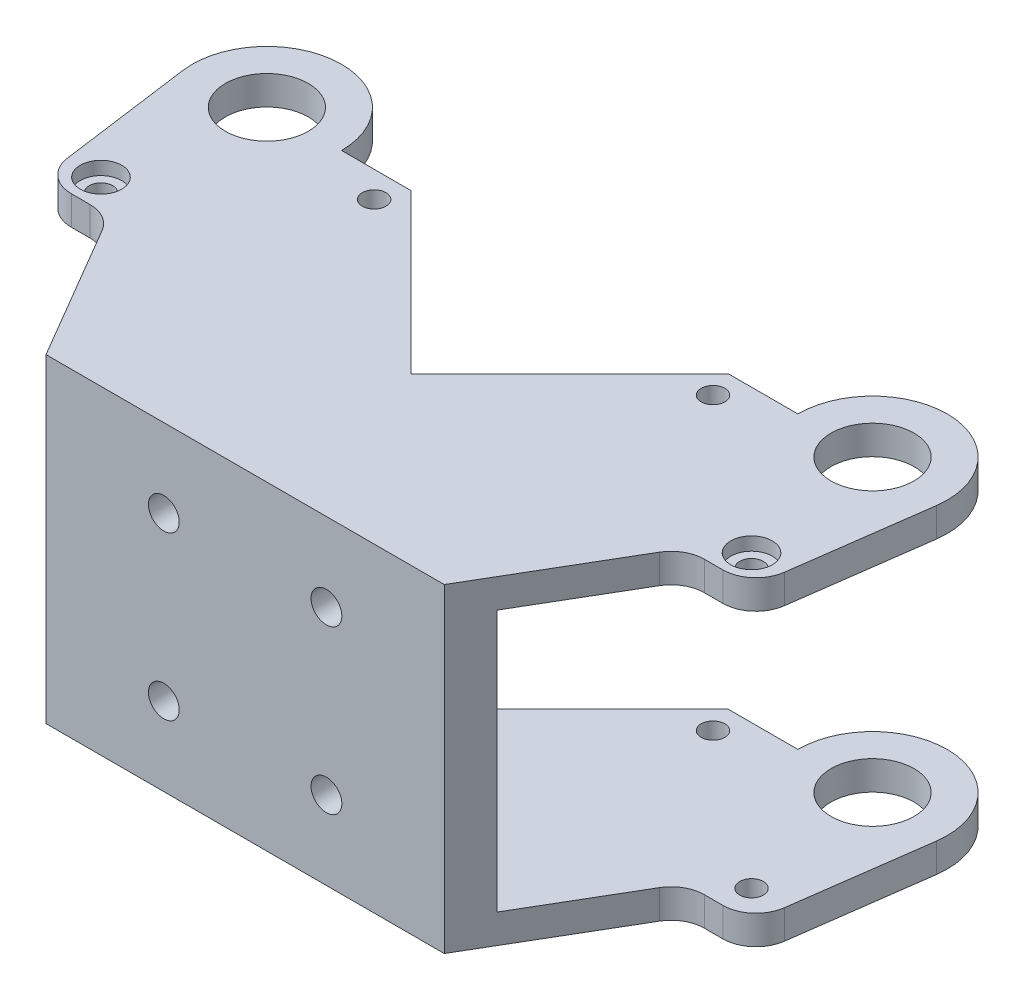
SolidWorks part; units mm, degrees
material "6061 Alloy"
ref_plane "Front Plane" through (0, 0, 0) normal (0, 0, 1) x (1, 0, 0)
ref_plane "Top Plane" through (0, 0, 0) normal (0, 1, 0) x (1, 0, 0)
ref_plane "Right Plane" through (0, 0, 0) normal (1, 0, 0) x (0, 0, -1)
sketch "Sketch1" plane through (0, 0, 0) normal (0, 1, 0) x (1, 0, 0)
  line L0 (0, 0) -> (17.4276, 0) construction
  line L1 (0, -3.175) -> (0, -19.05)
  line L2 (0, -19.05) -> (19.05, -19.05)
  line L3 (19.05, -19.05) -> (27.5732, -4.51)
  line L4 (0, -3.175) -> (15.175, 12)
  line L5 (15.175, 12) -> (21.8267, 12)
  line L6 (0, 0) -> (35355.3391, 35355.3391) construction
  line L7 (0, 0) -> (35355.3391, -35355.3391) construction
  line L8 (36.0484, 11.0322) -> (33.9232, -4.51)
  line L9 (27.5732, -4.51) -> (33.9232, -4.51)
  arc A0 (36.0484, 11.0322) -> (21.8267, 12) centre (28.9705, 12) ccw
  circle A1 centre (28.9705, 12) radius 3.9687
  dimension "D2" = 12
  dimension "D3" = 7.9375
  dimension "D4" = 14.2875
  dimension "D1" = 28.9705
  dimension "D5" = 19.05
  dimension "D6" = 3.175
  dimension "D7" = 19.05
  dimension "D8" = 12
  dimension "D9" = 90
  dimension "D10" = 45
  dimension "D11" = 16.51
  dimension "D12" = 6.35
extrude "Boss-Extrude1" add sketch "Sketch1" along normal mid plane 30.5723
sketch "Sketch3" plane through (0, 15.2861, 0) normal (0, 1, 0) x (1, 0, 0)
  line L0 (28.9705, 12) -> (28.9705, -49988) construction
  line L1 (33.6755, 12.1888) -> (-12907.2768, -48284.1025) construction
  line L2 (31.1179, -1.7234) -> (30.0261, -1.4309) construction
  circle A0 centre (31.1179, -1.7234) radius 1.1303
  circle A1 centre (28.9705, 12) radius 4.4958 construction
  dimension "D1" = 8.9916
  dimension "D2" = 2.2606
  dimension "D3" = 15
  dimension "D4" = 12.7
sketch "Sketch2" plane through (0, 0, 0) normal (1, 0, 0) x (0, 0, -1)
  line L0 (-19.05, 15.2861) -> (-19.05, -15.2861) construction
  line L1 (-15.875, 12.508) -> (19.1437, 12.508)
  line L2 (-15.875, 12.508) -> (-15.875, -12.508)
  line L3 (-15.875, -12.508) -> (19.1437, -12.508)
  line L4 (19.1437, 12.508) -> (19.1437, -12.508)
  line L5 (19.1438, -15.2861) -> (19.1438, 15.2861) construction
  point P10 (-15.875, 0)
  dimension "D1" = 25.016
  dimension "D2" = 3.175
extrude "Cut-Extrude1" cut sketch "Sketch2" against normal mid plane 81.3723
extrude "Cut-Extrude2" cut sketch "Sketch3" against normal through all
fillet "Fillet1" radius 3.175 4 edges at (27.5732, 13.8971, 4.51) (33.9232, 13.8971, 4.51) (27.5732, -13.8971, 4.51) (33.9232, -13.8971, 4.51)
sketch "Sketch9" plane through (0, -15.2861, 0) normal (0, -1, 0) x (1, 0, 0)
  circle A0 centre (16.2105, -9.5) radius 1.1303
  circle A1 centre (28.9705, -12) radius 3.9687 construction
  dimension "D1" = 2.5
  dimension "D2" = 12.76
  dimension "D3" = 2.2606
extrude "Cut-Extrude5" cut sketch "Sketch9" against normal through all
mirror "Mirror3" about plane through (0, 15.2861, 3.175) normal (1, 0, 0) of "Cut-Extrude5", "Boss-Extrude1", "Cut-Extrude1", "Cut-Extrude2", "Fillet1"
sketch "Sketch6" plane through (0, 15.2861, 0) normal (0, 1, 0) x (1, 0, 0)
  circle A0 centre (28.9705, 12) radius 3.9687 construction
  circle A1 centre (17.4705, 9) radius 2
  point P0 (17.4705, 9)
  dimension "D3" = 4
  dimension "D1" = 3
  dimension "D2" = 11.5
sketch "Sketch7" plane through (0, 0, 19.05) normal (0, 0, 1) x (1, 0, 0)
  line L0 (0, 0) -> (35355.3391, -35355.3391) construction
  line L1 (0, 0) -> (35355.3391, 35355.3391) construction
  line L2 (-19.05, 15.2861) -> (-19.05, -15.2861) construction
  circle A0 centre (0, 0) radius 11 construction
  circle A1 centre (-7.7782, 7.7782) radius 1.4732
  circle A2 centre (7.7782, 7.7782) radius 1.4732
  circle A3 centre (7.7782, -7.7782) radius 1.4732
  circle A4 centre (-7.7782, -7.7782) radius 1.4732
  dimension "D1" = 22
  dimension "D3" = 2.9464
  dimension "D2" = 45
extrude "Cut-Extrude3" cut sketch "Sketch7" against normal through all
sketch "Sketch8" plane through (0, 15.2861, 0) normal (0, 1, 0) x (1, 0, 0)
  circle A0 centre (31.1179, -1.7234) radius 1.9844
  circle A1 centre (-31.1179, -1.7234) radius 1.9844
  dimension "D1" = 3.9688
extrude "Cut-Extrude4" cut sketch "Sketch8" against normal blind 1.27
